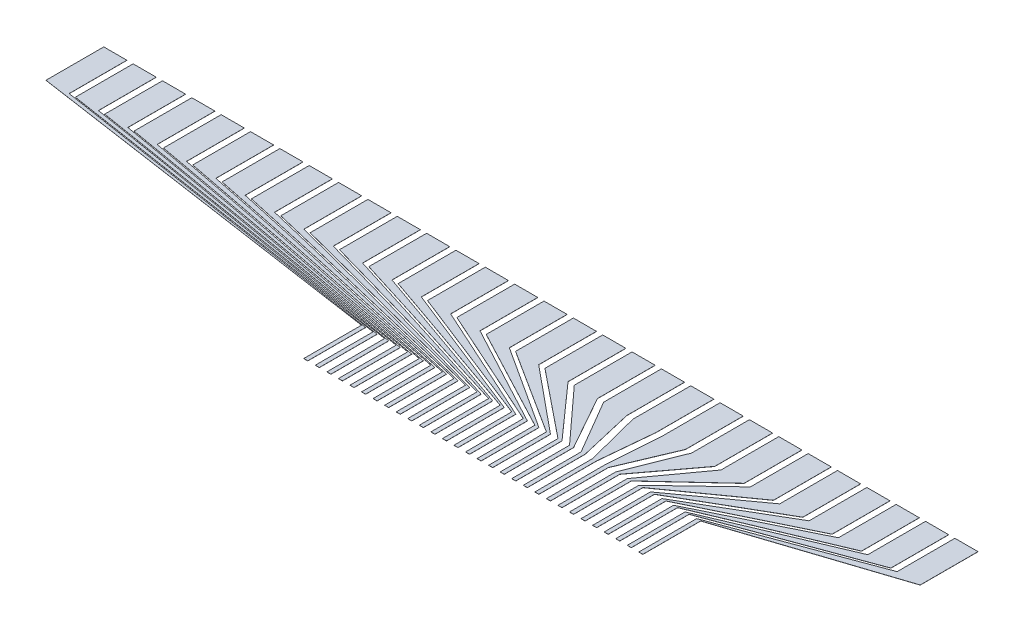
SolidWorks part; units mm, degrees
ref_plane "前视基准面" through (0, 0, 0) normal (0, 0, 1) x (1, 0, 0)
ref_plane "上视基准面" through (0, 0, 0) normal (0, 1, 0) x (1, 0, 0)
ref_plane "右视基准面" through (0, 0, 0) normal (1, 0, 0) x (0, 0, -1)
sketch "草图1" plane through (0, 0, 0) normal (0, 1, 0) x (1, 0, 0)
  line L0 (0, 0) -> (76.2, 0) construction
  line L1 (0, 0) -> (0, -25.4) construction
  line L2 (0, -25.4) -> (76.2, -25.4) construction
  line L3 (76.2, -25.4) -> (76.2, 0) construction
  line L4 (0, -12.7) -> (76.2, -12.7) construction
  line L5 (76.2, 0) -> (76.2, -5)
  line L7 (74.2, -5) -> (74.2, 0)
  line L8 (74.2, 0) -> (76.2, 0)
  line L9 (71.66, 0) -> (73.66, 0)
  line L10 (73.66, 0) -> (73.66, -5)
  line L12 (71.66, -5) -> (71.66, 0)
  line L13 (69.12, 0) -> (71.12, 0)
  line L14 (71.12, 0) -> (71.12, -5)
  line L16 (69.12, -5) -> (69.12, 0)
  line L17 (66.58, 0) -> (68.58, 0)
  line L18 (68.58, 0) -> (68.58, -5)
  line L20 (66.58, -5) -> (66.58, 0)
  line L21 (64.04, 0) -> (66.04, 0)
  line L22 (66.04, 0) -> (66.04, -5)
  line L24 (64.04, -5) -> (64.04, 0)
  line L25 (61.5, 0) -> (63.5, 0)
  line L26 (63.5, 0) -> (63.5, -5)
  line L28 (61.5, -5) -> (61.5, 0)
  line L29 (58.96, 0) -> (60.96, 0)
  line L30 (60.96, 0) -> (60.96, -5)
  line L32 (58.96, -5) -> (58.96, 0)
  line L33 (56.42, 0) -> (58.42, 0)
  line L34 (58.42, 0) -> (58.42, -5)
  line L36 (56.42, -5) -> (56.42, 0)
  line L37 (53.88, 0) -> (55.88, 0)
  line L38 (55.88, 0) -> (55.88, -5)
  line L40 (53.88, -5) -> (53.88, 0)
  line L41 (51.34, 0) -> (53.34, 0)
  line L42 (53.34, 0) -> (53.34, -5)
  line L44 (51.34, -5) -> (51.34, 0)
  line L45 (48.8, 0) -> (50.8, 0)
  line L46 (50.8, 0) -> (50.8, -5)
  line L48 (48.8, -5) -> (48.8, 0)
  line L49 (46.26, 0) -> (48.26, 0)
  line L50 (48.26, 0) -> (48.26, -5)
  line L52 (46.26, -5) -> (46.26, 0)
  line L53 (43.72, 0) -> (45.72, 0)
  line L54 (45.72, 0) -> (45.72, -5)
  line L56 (43.72, -5) -> (43.72, 0)
  line L57 (41.18, 0) -> (43.18, 0)
  line L58 (43.18, 0) -> (43.18, -5)
  line L60 (41.18, -5) -> (41.18, 0)
  line L61 (38.64, 0) -> (40.64, 0)
  line L62 (40.64, 0) -> (40.64, -5)
  line L64 (38.64, -5) -> (38.64, 0)
  line L65 (36.1, 0) -> (38.1, 0)
  line L66 (38.1, 0) -> (38.1, -5)
  line L68 (36.1, -5) -> (36.1, 0)
  line L69 (33.56, 0) -> (35.56, 0)
  line L70 (35.56, 0) -> (35.56, -5)
  line L72 (33.56, -5) -> (33.56, 0)
  line L73 (31.02, 0) -> (33.02, 0)
  line L74 (33.02, 0) -> (33.02, -5)
  line L76 (31.02, -5) -> (31.02, 0)
  line L77 (28.48, 0) -> (30.48, 0)
  line L78 (30.48, 0) -> (30.48, -5)
  line L80 (28.48, -5) -> (28.48, 0)
  line L81 (25.94, 0) -> (27.94, 0)
  line L82 (27.94, 0) -> (27.94, -5)
  line L84 (25.94, -5) -> (25.94, 0)
  line L85 (23.4, 0) -> (25.4, 0)
  line L86 (25.4, 0) -> (25.4, -5)
  line L88 (23.4, -5) -> (23.4, 0)
  line L89 (20.86, 0) -> (22.86, 0)
  line L90 (22.86, 0) -> (22.86, -5)
  line L92 (20.86, -5) -> (20.86, 0)
  line L93 (18.32, 0) -> (20.32, 0)
  line L94 (20.32, 0) -> (20.32, -5)
  line L96 (18.32, -5) -> (18.32, 0)
  line L97 (15.78, 0) -> (17.78, 0)
  line L98 (17.78, 0) -> (17.78, -5)
  line L100 (15.78, -5) -> (15.78, 0)
  line L101 (13.24, 0) -> (15.24, 0)
  line L102 (15.24, 0) -> (15.24, -5)
  line L104 (13.24, -5) -> (13.24, 0)
  line L105 (10.7, 0) -> (12.7, 0)
  line L106 (12.7, 0) -> (12.7, -5)
  line L108 (10.7, -5) -> (10.7, 0)
  line L109 (8.16, 0) -> (10.16, 0)
  line L110 (10.16, 0) -> (10.16, -5)
  line L112 (8.16, -5) -> (8.16, 0)
  line L113 (5.62, 0) -> (7.62, 0)
  line L114 (7.62, 0) -> (7.62, -5)
  line L116 (5.62, -5) -> (5.62, 0)
  line L117 (3.08, 0) -> (5.08, 0)
  line L118 (5.08, 0) -> (5.08, -5)
  line L120 (3.08, -5) -> (3.08, 0)
  line L121 (0.54, 0) -> (2.54, 0)
  line L122 (2.54, 0) -> (2.54, -5)
  line L124 (0.54, -5) -> (0.54, 0)
  line L361 (61.8976, -15.7) -> (61.8976, -9.7)
  line L362 (61.55, -9.7) -> (61.8976, -9.7) construction
  line L363 (61.55, -9.7) -> (61.55, -15.7)
  line L365 (60.8976, -15.7) -> (60.8976, -9.7)
  line L367 (60.55, -9.7) -> (60.55, -15.7)
  line L368 (59.8976, -15.7) -> (59.8976, -9.7)
  line L370 (59.55, -9.7) -> (59.55, -15.7)
  line L371 (58.8976, -15.7) -> (58.8976, -9.7)
  line L373 (58.55, -9.7) -> (58.55, -15.7)
  line L374 (57.8976, -15.7) -> (57.8976, -9.7)
  line L376 (57.55, -9.7) -> (57.55, -15.7)
  line L377 (56.8976, -15.7) -> (56.8976, -9.7)
  line L379 (56.55, -9.7) -> (56.55, -15.7)
  line L380 (55.8976, -15.7) -> (55.8976, -9.7)
  line L382 (55.55, -9.7) -> (55.55, -15.7)
  line L383 (54.8976, -15.7) -> (54.8976, -9.7)
  line L385 (54.55, -9.7) -> (54.55, -15.7)
  line L386 (53.8976, -15.7) -> (53.8976, -9.7)
  line L388 (53.55, -9.7) -> (53.55, -15.7)
  line L389 (52.8976, -15.7) -> (52.8976, -9.7)
  line L391 (52.55, -9.7) -> (52.55, -15.7)
  line L392 (51.8976, -15.7) -> (51.8976, -9.7)
  line L394 (51.55, -9.7) -> (51.55, -15.7)
  line L395 (50.8976, -15.7) -> (50.8976, -9.7)
  line L397 (50.55, -9.7) -> (50.55, -15.7)
  line L398 (49.8976, -15.7) -> (49.8976, -9.7)
  line L400 (49.55, -9.7) -> (49.55, -15.7)
  line L401 (48.8976, -15.7) -> (48.8976, -9.7)
  line L403 (48.55, -9.7) -> (48.55, -15.7)
  line L404 (47.8976, -15.7) -> (47.8976, -9.7)
  line L406 (47.55, -9.7) -> (47.55, -15.7)
  line L407 (46.8976, -15.7) -> (46.8976, -9.7)
  line L409 (46.55, -9.7) -> (46.55, -15.7)
  line L410 (45.8976, -15.7) -> (45.8976, -9.7)
  line L412 (45.55, -9.7) -> (45.55, -15.7)
  line L413 (44.8976, -15.7) -> (44.8976, -9.7)
  line L415 (44.55, -9.7) -> (44.55, -15.7)
  line L416 (43.8976, -15.7) -> (43.8976, -9.7)
  line L418 (43.55, -9.7) -> (43.55, -15.7)
  line L419 (42.8976, -15.7) -> (42.8976, -9.7)
  line L421 (42.55, -9.7) -> (42.55, -15.7)
  line L422 (41.8976, -15.7) -> (41.8976, -9.7)
  line L424 (41.55, -9.7) -> (41.55, -15.7)
  line L425 (40.8976, -15.7) -> (40.8976, -9.7)
  line L427 (40.55, -9.7) -> (40.55, -15.7)
  line L428 (39.8976, -15.7) -> (39.8976, -9.7)
  line L430 (39.55, -9.7) -> (39.55, -15.7)
  line L431 (38.8976, -15.7) -> (38.8976, -9.7)
  line L433 (38.55, -9.7) -> (38.55, -15.7)
  line L434 (37.8976, -15.7) -> (37.8976, -9.7)
  line L436 (37.55, -9.7) -> (37.55, -15.7)
  line L437 (36.8976, -15.7) -> (36.8976, -9.7)
  line L439 (36.55, -9.7) -> (36.55, -15.7)
  line L440 (35.8976, -15.7) -> (35.8976, -9.7)
  line L442 (35.55, -9.7) -> (35.55, -15.7)
  line L443 (34.8976, -15.7) -> (34.8976, -9.7)
  line L445 (34.55, -9.7) -> (34.55, -15.7)
  line L446 (33.8976, -15.7) -> (33.8976, -9.7)
  line L448 (33.55, -9.7) -> (33.55, -15.7)
  line L449 (32.8976, -15.7) -> (32.8976, -9.7)
  line L451 (32.55, -9.7) -> (32.55, -15.7)
  line L452 (74.2, -5) -> (61.55, -9.7)
  line L453 (61.8976, -9.7) -> (76.2, -5)
  line L454 (73.66, -5) -> (60.8976, -9.7)
  line L455 (60.55, -9.7) -> (71.66, -5)
  line L456 (71.12, -5) -> (59.8976, -9.7)
  line L457 (59.55, -9.7) -> (69.12, -5)
  line L458 (68.58, -5) -> (58.8976, -9.7)
  line L459 (66.58, -5) -> (58.55, -9.7)
  line L460 (57.8976, -9.7) -> (66.04, -5)
  line L461 (64.04, -5) -> (57.55, -9.7)
  line L462 (56.8976, -9.7) -> (63.5, -5)
  line L463 (61.5, -5) -> (56.55, -9.7)
  line L464 (58.96, -5) -> (55.55, -9.7)
  line L465 (60.96, -5) -> (55.8976, -9.7)
  line L466 (54.8976, -9.7) -> (58.42, -5)
  line L467 (54.55, -9.7) -> (56.42, -5)
  line L468 (55.88, -5) -> (53.8976, -9.7)
  line L469 (53.55, -9.7) -> (53.88, -5)
  line L470 (53.34, -5) -> (52.8976, -9.7)
  line L471 (52.55, -9.7) -> (51.34, -5)
  line L472 (50.8, -5) -> (51.8976, -9.7)
  line L473 (51.55, -9.7) -> (48.8, -5)
  line L474 (48.26, -5) -> (50.8976, -9.7)
  line L475 (50.55, -9.7) -> (46.26, -5)
  line L476 (45.72, -5) -> (49.8976, -9.7)
  line L477 (49.55, -9.7) -> (43.72, -5)
  line L478 (48.8976, -9.7) -> (43.18, -5)
  line L479 (41.18, -5) -> (48.55, -9.7)
  line L480 (47.8976, -9.7) -> (40.64, -5)
  line L481 (38.64, -5) -> (47.55, -9.7)
  line L482 (46.8976, -9.7) -> (38.1, -5)
  line L483 (36.1, -5) -> (46.55, -9.7)
  line L484 (45.8976, -9.7) -> (35.56, -5)
  line L485 (33.56, -5) -> (45.55, -9.7)
  line L486 (33.02, -5) -> (44.8976, -9.7)
  line L487 (44.55, -9.7) -> (31.02, -5)
  line L488 (30.48, -5) -> (43.8976, -9.7)
  line L489 (43.55, -9.7) -> (28.48, -5)
  line L490 (27.94, -5) -> (42.8976, -9.7)
  line L491 (42.55, -9.7) -> (25.94, -5)
  line L492 (25.4, -5) -> (41.8976, -9.7)
  line L493 (41.55, -9.7) -> (23.4, -5)
  line L494 (22.86, -5) -> (40.8976, -9.7)
  line L495 (40.55, -9.7) -> (20.86, -5)
  line L496 (20.32, -5) -> (39.8976, -9.7)
  line L497 (39.55, -9.7) -> (18.32, -5)
  line L498 (17.78, -5) -> (38.8976, -9.7)
  line L499 (38.55, -9.7) -> (15.78, -5)
  line L500 (15.24, -5) -> (37.8976, -9.7)
  line L501 (37.55, -9.7) -> (13.24, -5)
  line L502 (12.7, -5) -> (36.8976, -9.7)
  line L503 (36.55, -9.7) -> (10.7, -5)
  line L504 (10.16, -5) -> (35.8976, -9.7)
  line L505 (35.55, -9.7) -> (8.16, -5)
  line L506 (7.62, -5) -> (34.8976, -9.7)
  line L507 (34.55, -9.7) -> (5.62, -5)
  line L508 (5.08, -5) -> (33.8976, -9.7)
  line L509 (33.55, -9.7) -> (3.08, -5)
  line L510 (2.54, -5) -> (32.8976, -9.7)
  line L511 (32.55, -9.7) -> (0.54, -5)
  line L512 (32.55, -15.7) -> (32.8976, -15.7)
  line L513 (33.55, -15.7) -> (33.8976, -15.7)
  line L514 (34.55, -15.7) -> (34.8976, -15.7)
  line L515 (35.55, -15.7) -> (35.8976, -15.7)
  line L516 (36.55, -15.7) -> (36.8976, -15.7)
  line L517 (37.55, -15.7) -> (37.8976, -15.7)
  line L518 (38.55, -15.7) -> (38.8976, -15.7)
  line L519 (39.55, -15.7) -> (39.8976, -15.7)
  line L520 (40.55, -15.7) -> (40.8976, -15.7)
  line L521 (41.55, -15.7) -> (41.8976, -15.7)
  line L522 (42.55, -15.7) -> (42.8976, -15.7)
  line L523 (43.55, -15.7) -> (43.8976, -15.7)
  line L524 (44.55, -15.7) -> (44.8976, -15.7)
  line L525 (45.55, -15.7) -> (45.8976, -15.7)
  line L526 (46.55, -15.7) -> (46.8976, -15.7)
  line L527 (47.55, -15.7) -> (47.8976, -15.7)
  line L528 (48.55, -15.7) -> (48.8976, -15.7)
  line L529 (49.55, -15.7) -> (49.8976, -15.7)
  line L530 (50.55, -15.7) -> (50.8976, -15.7)
  line L531 (51.55, -15.7) -> (51.8976, -15.7)
  line L532 (52.55, -15.7) -> (52.8976, -15.7)
  line L533 (53.55, -15.7) -> (53.8976, -15.7)
  line L534 (54.55, -15.7) -> (54.8976, -15.7)
  line L535 (55.55, -15.7) -> (55.8976, -15.7)
  line L536 (56.55, -15.7) -> (56.8976, -15.7)
  line L537 (57.55, -15.7) -> (57.8976, -15.7)
  line L538 (58.55, -15.7) -> (58.8976, -15.7)
  line L539 (59.55, -15.7) -> (59.8976, -15.7)
  line L540 (60.55, -15.7) -> (60.8976, -15.7)
  line L541 (61.55, -15.7) -> (61.8976, -15.7)
  line L543 (62.55, -15.7) -> (62.8976, -15.7) [skipped]
  dimension "D1" = 30
  dimension "D2" = 30
  dimension "D3" = 31
extrude "凸台-拉伸1" add sketch "草图1" along normal blind 0.01
sketch "草图2" plane through (0, 0.01, 0) normal (0, 1, 0) x (1, 0, 0)
  line L0 (32.55, -15.7) -> (32.55, -14.7)
  line L1 (32.55, -9.7) -> (32.55, -15.7) construction
  line L2 (32.55, -14.7) -> (61.8976, -14.7)
  line L3 (61.8976, -15.7) -> (61.8976, -9.7) construction
  line L4 (61.8976, -14.7) -> (61.8976, -15.7)
  line L5 (61.8976, -15.7) -> (32.55, -15.7)
extrude "切除-拉伸1" cut sketch "草图2" against normal blind 10
